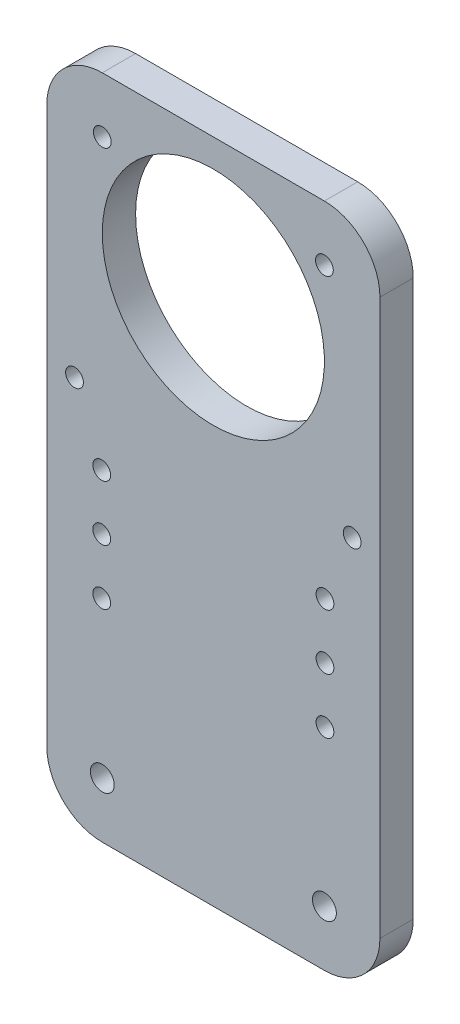
SolidWorks part; units mm, degrees
ref_plane "前视基准面" through (0, 0, 0) normal (0, 0, 1) x (1, 0, 0)
ref_plane "上视基准面" through (0, 0, 0) normal (0, 1, 0) x (1, 0, 0)
ref_plane "右视基准面" through (0, 0, 0) normal (1, 0, 0) x (0, 0, -1)
other "Configuration Table"
sketch "草图1" plane through (0, 0, 0) normal (0, 0, 1) x (1, 0, 0)
  line L0 (0, -60) -> (0, -50)
  line L5 (-30, -60) -> (30, -60)
  line L6 (-30, -60) -> (-30, 60)
  line L7 (0, -50) -> (20, -50)
  line L8 (-30, 60) -> (30, 60)
  line L9 (30, -60) -> (30, 60)
  line L10 (-30, -60) -> (30, 60) construction
  line L11 (-30, 60) -> (30, -60) construction
  line L12 (0, 60) -> (0, 10)
  line L13 (0, 35) -> (0, 42)
  line L14 (0, 42) -> (0, 28) construction
  line L15 (6, 42) -> (6, 28)
  line L16 (-6, 42) -> (-6, 28)
  circle A33 centre (0, 50.5) radius 1.6
  circle A34 centre (20, -50) radius 2.15
  circle A35 centre (-20, -50) radius 2.15
  circle A36 centre (0, 35) radius 19
  circle A37 centre (0, 35) radius 15.5
  circle A38 centre (13.4234, 42.75) radius 1.6
  circle A39 centre (13.4234, 27.25) radius 1.6
  circle A40 centre (0, 19.5) radius 1.6
  circle A41 centre (-13.4234, 27.25) radius 1.6
  circle A42 centre (-13.4234, 42.75) radius 1.6
  arc A43 (6, 42) -> (-6, 42) centre (0, 42) ccw
  arc A44 (-6, 28) -> (6, 28) centre (0, 28) ccw
  point P0 (0, 0)
  point P20 (0, 35)
  dimension "D5" = 4.3
  dimension "D8" = 31
  dimension "D9" = 3.2
  dimension "D10" = 6
  dimension "D13" = 6
  dimension "D7" = 38
  dimension "D1" = 60
  dimension "D2" = 120
  dimension "D3" = 10
  dimension "D4" = 20
  dimension "D6" = 50
  dimension "D11" = 7
  dimension "D12" = 14
extrude "凸台-拉伸3" add sketch "草图1" along normal blind 6
sketch "草图9" plane through (0, 0, 6) normal (0, 0, 1) x (1, 0, 0)
  line L0 (0, -972) -> (0, 49028) construction
  line L1 (-15, 28) -> (-15, -12)
  line L2 (-15, -12) -> (-20.1, -12)
  line L3 (-20, 28) -> (-20.1, -22)
  line L4 (-20.1, -22) -> (-25.1, -22)
  circle A0 centre (0, 28) radius 15
  circle A2 centre (-20.1, -12) radius 1.6
  circle A3 centre (20.1, -12) radius 1.6
  circle A4 centre (0, 28) radius 20
  circle A7 centre (-20.1, -2) radius 1.6
  circle A8 centre (20.1, -2) radius 1.6
  circle A13 centre (-20.1, -22) radius 1.6
  circle A14 centre (20.1, -22) radius 1.6
  dimension "D1" = 30
  dimension "D3" = 5.1
  dimension "D4" = 3.2
  dimension "D5" = 40
  dimension "D8" = 2
  dimension "D2" = 40
  dimension "D6" = 50
  dimension "D7" = 5
  dimension "D9" = 2
extrude "切除-拉伸1" cut sketch "草图9" against normal blind 6 contours A14 | A8 | A3 | A7 | A2 | A13
fillet "圆角1" radius 10 4 edges at (30, -60, 3) (-30, -60, 3) (30, 60, 3) (-30, 60, 3)
sketch "草图11" plane through (0, 0, 0) normal (0, 0, -1) x (-1, 0, 0)
  line L0 (0, 48) -> (0, 22)
  arc A0 (6, 42) -> (-6, 42) centre (0, 42) ccw construction
  arc A1 (-6, 28) -> (6, 28) centre (0, 28) ccw construction
  circle A2 centre (0, 35) radius 20
  circle M12 centre (-13.4234, 27.25) radius 1.6
  circle M13 centre (-13.4234, 42.75) radius 1.6
  circle M14 centre (13.4234, 27.25) radius 1.6
  circle M15 centre (0, 50.5) radius 1.6
  circle M16 centre (13.4234, 42.75) radius 1.6
  line M17 (6, 42) -> (6, 28)
  arc M18 (6, 28) -> (-6, 28) centre (0, 28) cw
  line M19 (-6, 28) -> (-6, 42)
  arc M20 (-6, 42) -> (6, 42) centre (0, 42) cw
  circle M21 centre (0, 19.5) radius 1.6
  dimension "D1" = 40
extrude "切除-拉伸2" cut sketch "草图11" against normal blind 6 contours A2 M12 M14 M16 M21 M20 M17 M18 M19 M15 M13
sketch "草图21" plane through (0, 0, 0) normal (0, 0, -1) x (-1, 0, 0)
  line L0 (-20, 60) -> (-20, 50)
  line L1 (-20, 50) -> (-30, 50)
  line L2 (0, -943.1857) -> (0, 49056.8143) construction
  line L3 (0, 35) -> (0, 10)
  line L4 (0, 10) -> (25, 10)
  circle A0 centre (-20, 50) radius 1.6
  circle A2 centre (20, 50) radius 1.6
  circle A3 centre (25, 10) radius 1.6
  circle A4 centre (-25, 10) radius 1.6
  dimension "D1" = 3.2
  dimension "D4" = 3.2
  dimension "D2" = 25
  dimension "D3" = 25
extrude "切除-拉伸7" cut sketch "草图21" against normal blind 10 contours A4 | A3 | A2 | A0
